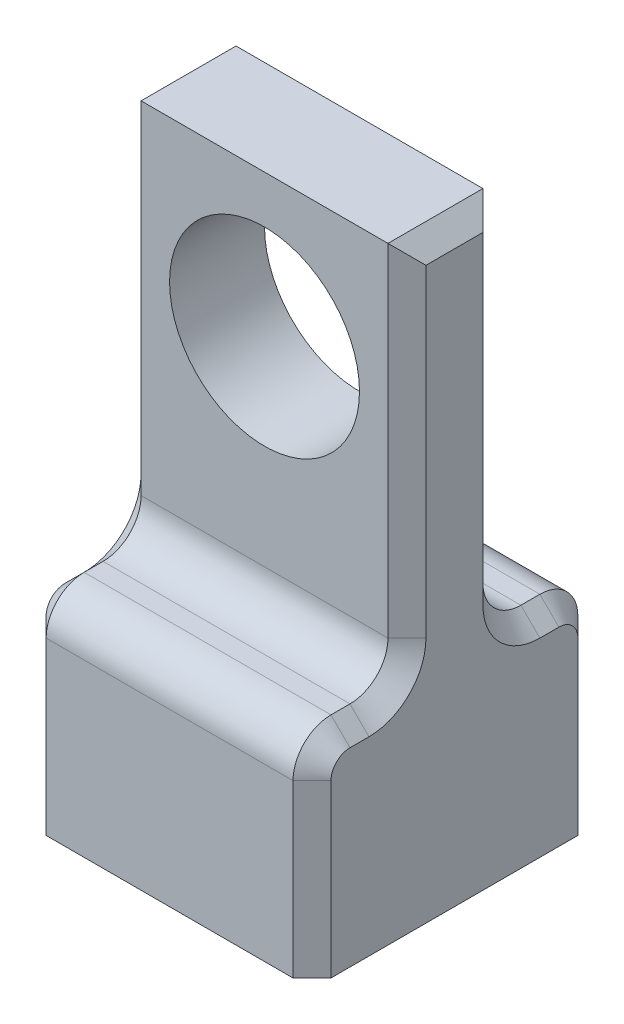
SolidWorks part; units mm, degrees
ref_plane "Front Plane" through (0, 0, 0) normal (0, 0, 1) x (1, 0, 0)
ref_plane "Top Plane" through (0, 0, 0) normal (0, 1, 0) x (1, 0, 0)
ref_plane "Right Plane" through (0, 0, 0) normal (1, 0, 0) x (0, 0, -1)
sketch "Sketch1" plane through (0, 0, 0) normal (0, 1, 0) x (1, 0, 0)
  line L1 (7.5, 7.5) -> (-7.5, 7.5)
  line L2 (7.5, 7.5) -> (7.5, -7.5)
  line L3 (7.5, -7.5) -> (-7.5, -7.5)
  line L4 (-7.5, 7.5) -> (-7.5, -7.5)
  line L5 (7.5, 7.5) -> (-7.5, -7.5) construction
  line L6 (7.5, -7.5) -> (-7.5, 7.5) construction
  point P0 (0, 0)
  dimension "D1" = 15
  dimension "D2" = 15
extrude "Boss-Extrude1" add sketch "Sketch1" along normal blind 31
sketch "Sketch2" plane through (0, 0, 7.5) normal (0, 0, 1) x (1, 0, 0)
  line L0 (-7.5, 0) -> (7.5, 0) construction
  circle A0 centre (0, 23.5) radius 5
  dimension "D1" = 10
  dimension "D2" = 23.5
extrude "Cut-Extrude1" cut sketch "Sketch2" against normal blind 25
sketch "Sketch3" plane through (0, 31, 0) normal (0, 1, 0) x (1, 0, 0)
  line L0 (7.5, -7.5) -> (7.5, 7.5) construction
  line L1 (-7.5, 7.5) -> (7.5, 7.5)
  line L2 (-7.5, 7.5) -> (-7.5, 2.5)
  line L3 (-7.5, 2.5) -> (7.5, 2.5)
  line L4 (7.5, 7.5) -> (7.5, 2.5)
  line L5 (-7.5, 7.5) -> (-7.5, -7.5) construction
  line L6 (7.5, -7.5) -> (-7.5, -7.5)
  line L7 (7.5, -7.5) -> (7.5, -2.5)
  line L8 (7.5, -2.5) -> (-7.5, -2.5)
  line L9 (-7.5, -7.5) -> (-7.5, -2.5)
  dimension "D1" = 5
  dimension "D2" = 5
  dimension "D3" = 5
extrude "Cut-Extrude2" cut sketch "Sketch3" against normal blind 20
fillet "Fillet4" radius 2 4 edges at (0, 11, 7.5) (0, 11, -7.5) (0, 11, -2.5) (0, 11, 2.5)
chamfer "Chamfer1" distance 1 angle 45 22 edges at (7.5, 31, 0) (-7.5, 31, 0) (-7.5, 4.5, 7.5) (-7.5, 10.4142, 6.9142) (-7.5, 11, 5) (-7.5, 22, 2.5) (-7.5, 11.5858, 3.0858) (-7.5, 22, -2.5) (-7.5, 11.5858, -3.0858) (-7.5, 11, -5) (-7.5, 4.5, -7.5) (-7.5, 10.4142, -6.9142) (7.5, 4.5, -7.5) (7.5, 10.4142, -6.9142) (7.5, 11, -5) (7.5, 22, -2.5) (7.5, 11.5858, -3.0858) (7.5, 22, 2.5) (7.5, 11.5858, 3.0858) (7.5, 11, 5) (7.5, 4.5, 7.5) (7.5, 10.4142, 6.9142)
sketch "Sketch4" plane through (0, 0, 0) normal (0, -1, 0) x (1, 0, 0)
  line L0 (-6.5, 7.5) -> (6.5, 7.5) construction
  circle A0 centre (0, 4) radius 1.5
  circle A1 centre (0, -4) radius 1.5
  dimension "D1" = 3
  dimension "D2" = 3
  dimension "D3" = 8
  dimension "D4" = 3.5
extrude "Cut-Extrude3" cut sketch "Sketch4" against normal blind 10
